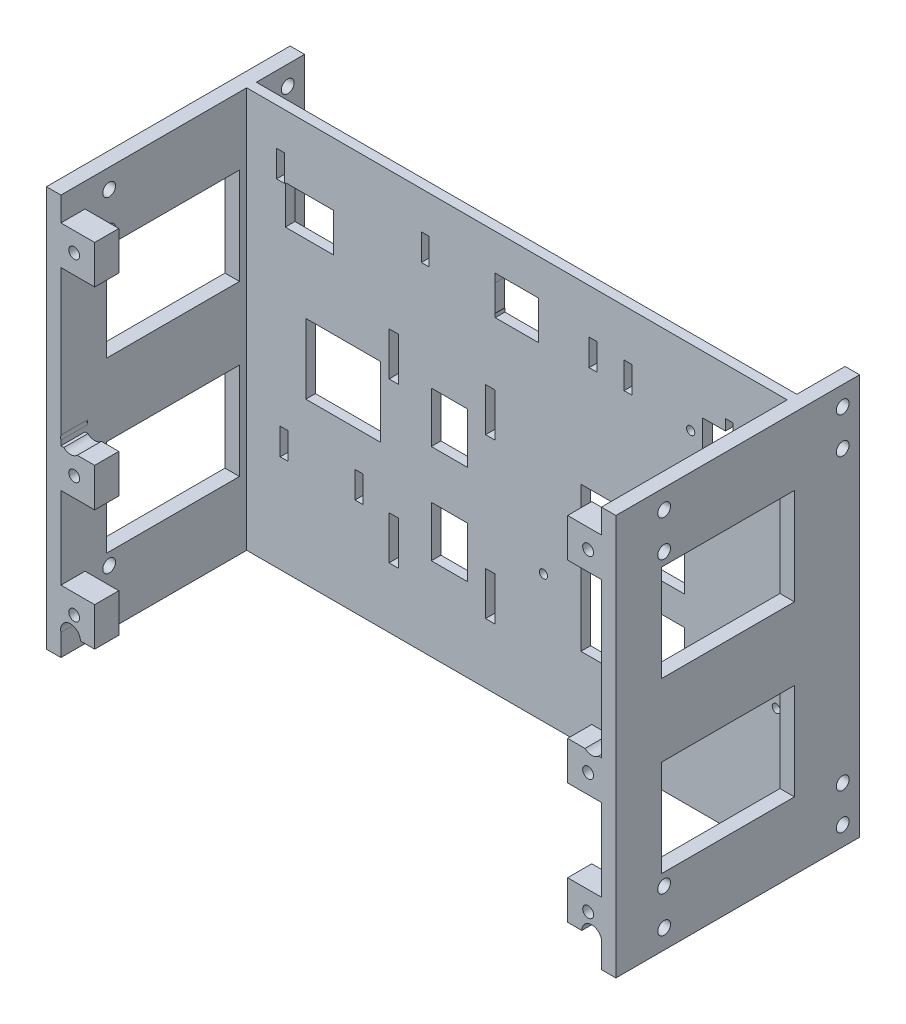
SolidWorks part; units mm, degrees
ref_plane "前视基准面" through (0, 0, 0) normal (0, 0, 1) x (1, 0, 0)
ref_plane "上视基准面" through (0, 0, 0) normal (0, 1, 0) x (1, 0, 0)
ref_plane "右视基准面" through (0, 0, 0) normal (1, 0, 0) x (0, 0, -1)
other "Configuration Table"
sketch "Sketch_Bottom_pan" plane through (0, 0, 0) normal (0, 0, 1) x (1, 0, 0)
  line L0 (118, -83) -> (118, 83)
  line L1 (118, 83) -> (-118, 83)
  line L2 (-118, 83) -> (-118, -83)
  line L3 (-118, -83) -> (118, -83)
extrude "Bottom_pan" add sketch "Sketch_Bottom_pan" along normal blind 4 from offset 49
sketch "Sketch_Side_rails" plane through (0, 0, 0) normal (0, 0, 1) x (1, 0, 0)
  line L0 (-118, -83) -> (-118, 83)
  line L1 (-118, 83) -> (-112, 83)
  line L2 (-112, 83) -> (-112, -83)
  line L3 (-112, -83) -> (-118, -83)
  line L4 (112, -83) -> (112, 83)
  line L5 (112, 83) -> (118, 83)
  line L6 (118, 83) -> (118, -83)
  line L7 (118, -83) -> (112, -83)
extrude "Side_rails" add sketch "Sketch_Side_rails" along normal blind 101 from offset 69
sketch "Sketch_Floor_vents_and_strap_slots" plane through (0, 0, 0) normal (0, 0, 1) x (1, 0, 0)
  line L0 (-49, -58) -> (-53, -58)
  line L1 (-53, -58) -> (-53, -40)
  line L2 (-53, -40) -> (-49, -40)
  line L3 (-49, -40) -> (-49, -58)
  line L4 (-20.5, -48.5) -> (-35.5, -48.5)
  line L5 (-35.5, -48.5) -> (-35.5, -27.5)
  line L6 (-35.5, -27.5) -> (-20.5, -27.5)
  line L7 (-20.5, -27.5) -> (-20.5, -48.5)
  line L8 (-94.9, -42.5) -> (-98.1, -42.5)
  line L9 (-98.1, -42.5) -> (-98.1, -31.5)
  line L10 (-98.1, -31.5) -> (-94.9, -31.5)
  line L11 (-94.9, -31.5) -> (-94.9, -42.5)
  line L12 (-67.1, -42.5) -> (-67.1, -31.5)
  line L13 (-67.1, -31.5) -> (-63.9, -31.5)
  line L14 (-63.9, -31.5) -> (-63.9, -42.5)
  line L15 (-63.9, -42.5) -> (-67.1, -42.5)
  line L16 (-87.5, -16.5) -> (-87.5, 12.5)
  line L17 (-87.5, 12.5) -> (-56.5, 12.5)
  line L18 (-56.5, 12.5) -> (-56.5, -16.5)
  line L19 (-56.5, -16.5) -> (-87.5, -16.5)
  line L20 (-20.5, -7.5) -> (-35.5, -7.5)
  line L21 (-35.5, -7.5) -> (-35.5, 13.5)
  line L22 (-35.5, 13.5) -> (-20.5, 13.5)
  line L23 (-20.5, 13.5) -> (-20.5, -7.5)
  line L24 (-49, 8) -> (-53, 8)
  line L25 (-53, 8) -> (-53, 26)
  line L26 (-53, 26) -> (-49, 26)
  line L27 (-49, 26) -> (-49, 8)
  line L28 (-76, 41) -> (-96, 41)
  line L29 (-96, 41) -> (-96, 57)
  line L30 (-96, 57) -> (-76, 57)
  line L31 (-76, 57) -> (-76, 41)
  line L32 (-99.6, 56.5) -> (-99.6, 67.5)
  line L33 (-99.6, 67.5) -> (-96.4, 67.5)
  line L34 (-96.4, 67.5) -> (-96.4, 56.5)
  line L35 (-96.4, 56.5) -> (-99.6, 56.5)
  line L36 (-39.6, 56.5) -> (-39.6, 67.5)
  line L37 (-39.6, 67.5) -> (-36.4, 67.5)
  line L38 (-36.4, 67.5) -> (-36.4, 56.5)
  line L39 (-36.4, 56.5) -> (-39.6, 56.5)
  line L40 (-9, -58) -> (-13, -58)
  line L41 (-13, -58) -> (-13, -40)
  line L42 (-13, -40) -> (-9, -40)
  line L43 (-9, -40) -> (-9, -58)
  line L44 (69.5, -50) -> (26.5, -50)
  line L45 (26.5, -50) -> (26.5, -20)
  line L46 (26.5, -20) -> (69.5, -20)
  line L47 (69.5, -20) -> (69.5, -50)
  line L48 (69.5, -8) -> (26.5, -8)
  line L49 (26.5, -8) -> (26.5, 10)
  line L50 (26.5, 10) -> (69.5, 10)
  line L51 (69.5, 10) -> (69.5, -8)
  line L52 (-13, 8) -> (-13, 26)
  line L53 (-13, 26) -> (-9, 26)
  line L54 (-9, 26) -> (-9, 8)
  line L55 (-9, 8) -> (-13, 8)
  line L56 (77, 45) -> (77, 59)
  line L57 (77, 59) -> (86.4, 59)
  line L58 (86.4, 59) -> (86.4, 63.5)
  line L59 (86.4, 63.5) -> (89.6, 63.5)
  line L60 (89.6, 63.5) -> (89.6, 59)
  line L61 (89.6, 59) -> (95, 59)
  line L62 (95, 59) -> (95, 45)
  line L63 (95, 45) -> (77, 45)
  line L64 (47.6, 52.5) -> (44.4, 52.5)
  line L65 (44.4, 52.5) -> (44.4, 63.5)
  line L66 (44.4, 63.5) -> (47.6, 63.5)
  line L67 (47.6, 63.5) -> (47.6, 52.5)
  line L68 (-9, 68) -> (9, 68)
  line L69 (9, 68) -> (9, 52)
  line L70 (9, 52) -> (-9, 52)
  line L71 (-9, 52) -> (-9, 53.5)
  line L72 (-9, 53.5) -> (-9.1, 53.5)
  line L73 (-9.1, 53.5) -> (-9.1, 64.5)
  line L74 (-9.1, 64.5) -> (-9, 64.5)
  line L75 (-9, 64.5) -> (-9, 68)
  line L76 (29.9, 53.5) -> (29.9, 64.5)
  line L77 (29.9, 64.5) -> (33.1, 64.5)
  line L78 (33.1, 64.5) -> (33.1, 53.5)
  line L79 (33.1, 53.5) -> (29.9, 53.5)
extrude "Floor_vents_and_strap_slots" cut sketch "Sketch_Floor_vents_and_strap_slots" along normal blind 7 from offset 50
sketch "Sketch_Rail_windows" plane through (0, 0, 0) normal (0, 0, 1) x (1, 0, 0)
  line L0 (-119.5, -15) -> (-110.5, -15)
  line L1 (-110.5, -15) -> (-110.5, -55)
  line L2 (-110.5, -55) -> (-119.5, -55)
  line L3 (-119.5, -55) -> (-119.5, -15)
  line L4 (110.5, -15) -> (119.5, -15)
  line L5 (119.5, -15) -> (119.5, -55)
  line L6 (119.5, -55) -> (110.5, -55)
  line L7 (110.5, -55) -> (110.5, -15)
  line L8 (-119.5, 55) -> (-110.5, 55)
  line L9 (-110.5, 55) -> (-110.5, 15)
  line L10 (-110.5, 15) -> (-119.5, 15)
  line L11 (-119.5, 15) -> (-119.5, 55)
  line L12 (110.5, 55) -> (119.5, 55)
  line L13 (119.5, 55) -> (119.5, 15)
  line L14 (119.5, 15) -> (110.5, 15)
  line L15 (110.5, 15) -> (110.5, 55)
extrude "Rail_windows" cut sketch "Sketch_Rail_windows" along normal blind 55 from offset 42
sketch "Sketch_Hip_M5_cross_bores" plane through (0, 0, 0) normal (1, 0, 0) x (0, 0, -1)
  circle A0 centre (62, -75) radius 2.65
  circle A1 centre (-12, -75) radius 2.65
  circle A2 centre (62, -60) radius 2.65
  circle A3 centre (-12, -60) radius 2.65
  circle A4 centre (62, 60) radius 2.65
  circle A5 centre (-12, 60) radius 2.65
  circle A6 centre (62, 75) radius 2.65
  circle A7 centre (-12, 75) radius 2.65
extrude "Hip_M5_cross_bores" cut sketch "Sketch_Hip_M5_cross_bores" along normal blind 240 from offset 120
sketch "Sketch_Six_deck_bosses" plane through (0, 0, 0) normal (0, 0, 1) x (1, 0, 0)
  line L0 (-118, -57) -> (-98, -57)
  line L1 (-98, -57) -> (-98, -73)
  line L2 (-98, -73) -> (-118, -73)
  line L3 (-118, -73) -> (-118, -57)
  line L4 (118, -57) -> (118, -73)
  line L5 (118, -73) -> (98, -73)
  line L6 (98, -73) -> (98, -57)
  line L7 (98, -57) -> (118, -57)
  line L8 (-98, -7) -> (-98, -23)
  line L9 (-98, -23) -> (-118, -23)
  line L10 (-118, -23) -> (-118, -7)
  line L11 (-118, -7) -> (-98, -7)
  line L12 (98, -7) -> (118, -7)
  line L13 (118, -7) -> (118, -23)
  line L14 (118, -23) -> (98, -23)
  line L15 (98, -23) -> (98, -7)
  line L16 (-98, 73) -> (-98, 57)
  line L17 (-98, 57) -> (-118, 57)
  line L18 (-118, 57) -> (-118, 73)
  line L19 (-118, 73) -> (-98, 73)
  line L20 (118, 73) -> (118, 57)
  line L21 (118, 57) -> (98, 57)
  line L22 (98, 57) -> (98, 73)
  line L23 (98, 73) -> (118, 73)
extrude "Six_deck_bosses" add sketch "Sketch_Six_deck_bosses" along normal blind 10 from offset 22
sketch "Sketch_Power_tray_M3" plane through (0, 0, 0) normal (0, 0, 1) x (1, 0, 0)
  circle A0 centre (11, -30) radius 1.7
  circle A1 centre (107.5, -30) radius 1.7
  circle A2 centre (72, 52) radius 1.7
  dimension "D1" = 3.4
  dimension "D4" = 3.4
  dimension "D7" = 3.4
  dimension "D2" = 11
  dimension "D3" = 30
  dimension "D5" = 107.5
  dimension "D6" = 30
  dimension "D8" = 72
  dimension "D9" = 52
extrude "Power_tray_M3" cut sketch "Sketch_Power_tray_M3" along normal blind 7 from offset 50
sketch "Sketch_Deck_M4_clearance" plane through (0, 0, 0) normal (0, 0, 1) x (1, 0, 0)
  circle A0 centre (-106.5, -65) radius 2.25
  circle A1 centre (-106.5, -15) radius 2.25
  circle A2 centre (-106.5, 65) radius 2.25
  circle A3 centre (106.5, -65) radius 2.25
  circle A4 centre (106.5, -15) radius 2.25
  circle A5 centre (106.5, 65) radius 2.25
  dimension "D1" = 4.5
  dimension "D4" = 4.5
  dimension "D7" = 4.5
  dimension "D10" = 4.5
  dimension "D13" = 4.5
  dimension "D16" = 4.5
  dimension "D2" = 106.5
  dimension "D3" = 65
  dimension "D5" = 106.5
  dimension "D6" = 15
  dimension "D8" = 106.5
  dimension "D9" = 65
  dimension "D11" = 106.5
  dimension "D12" = 65
  dimension "D14" = 106.5
  dimension "D15" = 15
  dimension "D17" = 106.5
  dimension "D18" = 65
extrude "Deck_M4_clearance" cut sketch "Sketch_Deck_M4_clearance" along normal blind 12 from offset 21
sketch "Sketch_MID_head_and_tool_passages" plane through (0, 0, 0) normal (0, 0, 1) x (1, 0, 0)
  circle A0 centre (-108, -73) radius 4.1
  circle A1 centre (-108, -4) radius 4.1
  circle A2 centre (108, -73) radius 4.1
  circle A3 centre (108, -4) radius 4.1
  dimension "D1" = 8.2
  dimension "D4" = 8.2
  dimension "D7" = 8.2
  dimension "D10" = 8.2
  dimension "D2" = 108
  dimension "D3" = 73
  dimension "D5" = 108
  dimension "D6" = 4
  dimension "D8" = 108
  dimension "D9" = 73
  dimension "D11" = 108
  dimension "D12" = 4
extrude "MID_head_and_tool_passages" cut sketch "Sketch_MID_head_and_tool_passages" along normal blind 12 from offset 21
sketch "Sketch_M4_hex_capture_AF7p3" plane through (0, 0, 0) normal (0, 0, 1) x (1, 0, 0)
  line L0 (-102.2853, -65) -> (-104.3927, -61.35)
  line L1 (-104.3927, -61.35) -> (-108.6073, -61.35)
  line L2 (-108.6073, -61.35) -> (-110.7147, -65)
  line L3 (-110.7147, -65) -> (-108.6073, -68.65)
  line L4 (-108.6073, -68.65) -> (-104.3927, -68.65)
  line L5 (-104.3927, -68.65) -> (-102.2853, -65)
  line L6 (-102.2853, -15) -> (-104.3927, -11.35)
  line L7 (-104.3927, -11.35) -> (-108.6073, -11.35)
  line L8 (-108.6073, -11.35) -> (-110.7147, -15)
  line L9 (-110.7147, -15) -> (-108.6073, -18.65)
  line L10 (-108.6073, -18.65) -> (-104.3927, -18.65)
  line L11 (-104.3927, -18.65) -> (-102.2853, -15)
  line L12 (-102.2853, 65) -> (-104.3927, 68.65)
  line L13 (-104.3927, 68.65) -> (-108.6073, 68.65)
  line L14 (-108.6073, 68.65) -> (-110.7147, 65)
  line L15 (-110.7147, 65) -> (-108.6073, 61.35)
  line L16 (-108.6073, 61.35) -> (-104.3927, 61.35)
  line L17 (-104.3927, 61.35) -> (-102.2853, 65)
  line L18 (110.7147, -65) -> (108.6073, -61.35)
  line L19 (108.6073, -61.35) -> (104.3927, -61.35)
  line L20 (104.3927, -61.35) -> (102.2853, -65)
  line L21 (102.2853, -65) -> (104.3927, -68.65)
  line L22 (104.3927, -68.65) -> (108.6073, -68.65)
  line L23 (108.6073, -68.65) -> (110.7147, -65)
  line L24 (110.7147, -15) -> (108.6073, -11.35)
  line L25 (108.6073, -11.35) -> (104.3927, -11.35)
  line L26 (104.3927, -11.35) -> (102.2853, -15)
  line L27 (102.2853, -15) -> (104.3927, -18.65)
  line L28 (104.3927, -18.65) -> (108.6073, -18.65)
  line L29 (108.6073, -18.65) -> (110.7147, -15)
  line L30 (110.7147, 65) -> (108.6073, 68.65)
  line L31 (108.6073, 68.65) -> (104.3927, 68.65)
  line L32 (104.3927, 68.65) -> (102.2853, 65)
  line L33 (102.2853, 65) -> (104.3927, 61.35)
  line L34 (104.3927, 61.35) -> (108.6073, 61.35)
  line L35 (108.6073, 61.35) -> (110.7147, 65)
extrude "M4_hex_capture_AF7p3" cut sketch "Sketch_M4_hex_capture_AF7p3" along normal blind 4.4 from offset 21
